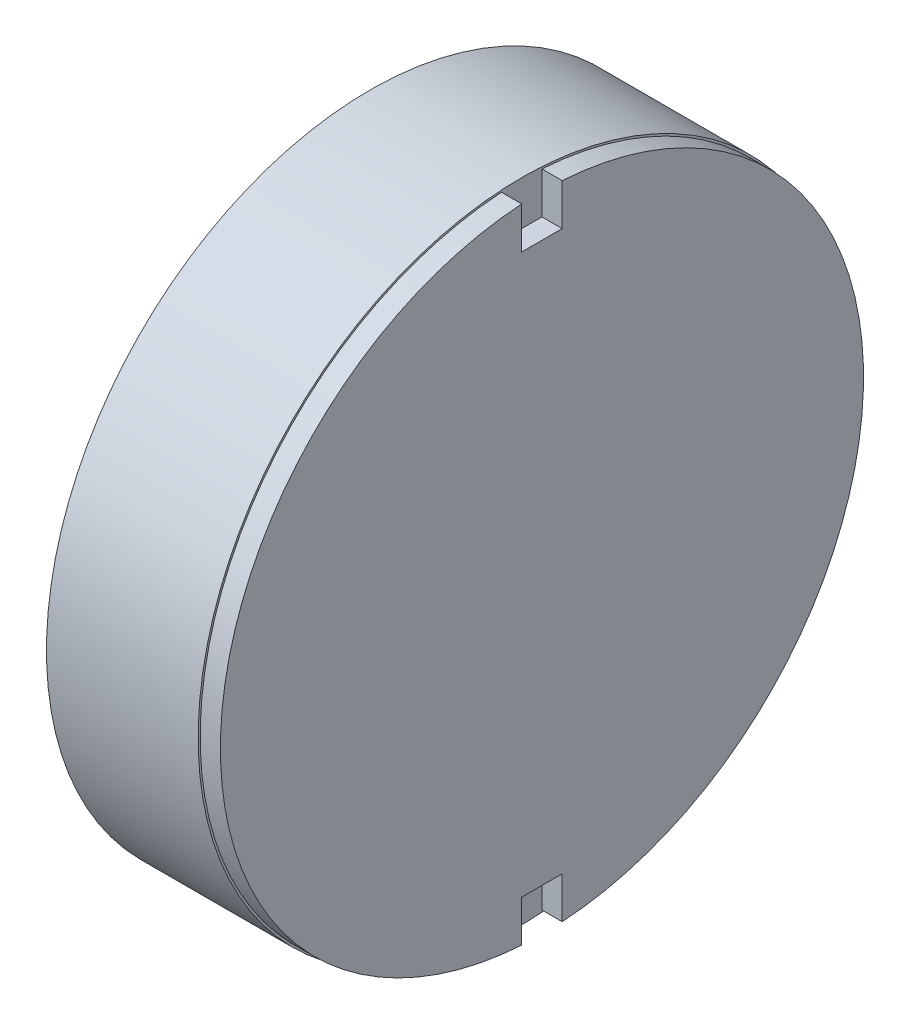
SolidWorks part; units mm, degrees
ref_plane "前视基准面" through (0, 0, 0) normal (0, 0, 1) x (1, 0, 0)
ref_plane "上视基准面" through (0, 0, 0) normal (0, 1, 0) x (1, 0, 0)
ref_plane "右视基准面" through (0, 0, 0) normal (1, 0, 0) x (0, 0, -1)
sketch "Sketch1" plane through (0, 0, 0) normal (1, 0, 0) x (0, 0, -1)
  circle A0 centre (0, 0) radius 16
extrude "Boss-Extrude1" add sketch "Sketch1" along normal blind 8.5
ref_axis "Axis1" through (8.5, 0, 0) along (-1, 0, 0)
sketch "Sketch2" plane through (0, 0, 0) normal (0, 0, 1) x (1, 0, 0)
  line L1 (8.5, 16) -> (7.5, 16)
  line L2 (8.5, 16) -> (8.5, 15.9)
  line L3 (8.5, 15.9) -> (7.5, 15.9)
  line L4 (7.5, 16) -> (7.5, 15.9)
  dimension "D1" = 1
  dimension "D2" = 0.1
revolve "Cut-Revolve1" cut sketch "Sketch2" angle 360 about axis through (8.5, 0, 0) along (-1, 0, 0)
sketch "Sketch3" plane through (8.5, 0, 0) normal (1, 0, 0) x (0, 0, -1)
  line L0 (0, 17.5657) -> (0, -21.7518) construction
  line L1 (-1, 15.8141) -> (-1, 17.8141)
  line L3 (-1, 15.8141) -> (-1, 13.8141)
  line L4 (-1, 13.8141) -> (1, 13.8141)
  line L5 (1, 15.8141) -> (1, 13.8141)
  line L6 (-1, 15.8141) -> (1, 13.8141) construction
  line L7 (-1, 13.8141) -> (1, 15.8141) construction
  line L8 (-1, 17.8141) -> (1, 17.8141)
  line L9 (1, 17.8141) -> (1, 15.8141)
  line L10 (-15.4635, 0) -> (13.0207, 0) construction
  line L11 (1, -17.8141) -> (1, -15.8141)
  line L12 (-1, -17.8141) -> (1, -17.8141)
  line L13 (-1, -15.8141) -> (-1, -17.8141)
  line L14 (-1, -15.8141) -> (-1, -13.8141)
  line L15 (-1, -13.8141) -> (1, -13.8141)
  line L16 (1, -15.8141) -> (1, -13.8141)
  point P3 (0, 14.8141)
  dimension "D1" = 2
  dimension "D2" = 2
  dimension "D3" = 2
extrude "Cut-Extrude1" cut sketch "Sketch3" against normal blind 1
